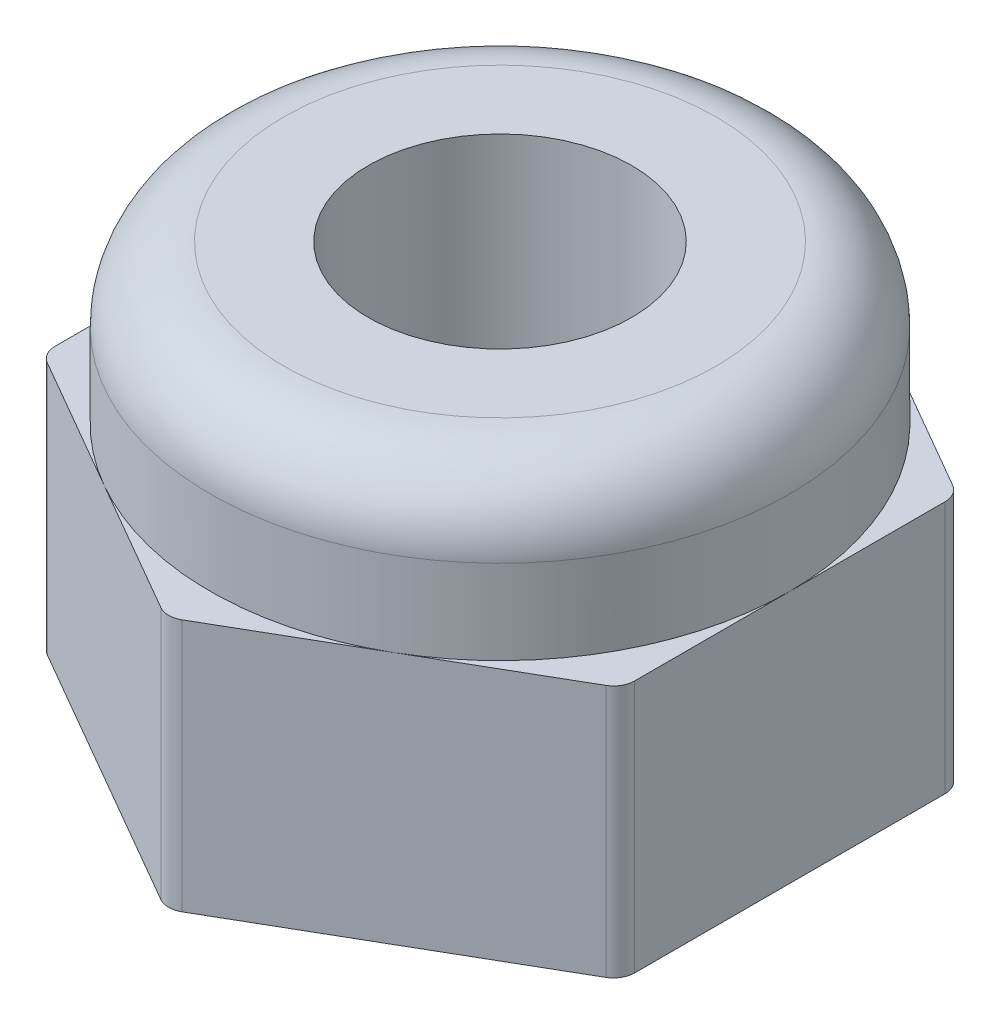
SolidWorks part; units mm, degrees
ref_plane "前视基准面" through (0, 0, 0) normal (0, 0, 1) x (1, 0, 0)
ref_plane "上视基准面" through (0, 0, 0) normal (0, 1, 0) x (1, 0, 0)
ref_plane "右视基准面" through (0, 0, 0) normal (1, 0, 0) x (0, 0, -1)
sketch "草图1" plane through (0, 0, 0) normal (0, 1, 0) x (1, 0, 0)
  line L1 (2.75, 1.5877) -> (0, 3.1754)
  line L2 (0, 3.1754) -> (-2.75, 1.5877)
  line L3 (-2.75, 1.5877) -> (-2.75, -1.5877)
  line L4 (-2.75, -1.5877) -> (0, -3.1754)
  line L5 (0, -3.1754) -> (2.75, -1.5877)
  line L6 (2.75, -1.5877) -> (2.75, 1.5877)
  circle A0 centre (0, 0) radius 2.75 construction
  dimension "D1" = 5.5
extrude "凸台-拉伸1" add sketch "草图1" along normal blind 2.4
sketch "草图2" plane through (0, 0, 0) normal (0, -1, 0) x (1, 0, 0)
  line L0 (2.75, 1.5877) -> (2.75, -1.5877) construction
  circle A0 centre (0, 0) radius 2.75
extrude "凸台-拉伸2" add sketch "草图2" against normal blind 3.9
fillet "圆角1" radius 0.7 1 edges at (0, 3.9, -2.75)
fillet "圆角2" radius 0.2 6 edges at (-2.75, 1.2, 1.5877) (-2.75, 1.2, -1.5877) (0, 1.2, -3.1754) (2.75, 1.2, -1.5877) (2.75, 1.2, 1.5877) (0, 1.2, 3.1754)
hole_wizard "M3 螺纹孔1" positions "草图3" profile "草图4" tap size "M3" standard "GB"
sketch "草图3" plane through (0, 0, 0) normal (0, -1, 0) x (-1, 0, 0)
  point P0 (0, 0)
cosmetic thread "孔螺蚊线1" parameters "D1"=6, "D2"=3
sketch "草图4" plane through (0, 0, 0) normal (1, 0, 0) x (0, 0, -1)
  line L0 (0, 0) -> (0, 8.2511)
  line L1 (0, 8.2511) -> (1.25, 7.5)
  line L2 (1.25, 7.5) -> (1.25, 0)
  line L5 (1.25, 0) -> (0, 0)
  line L10 (0, 8.2511) -> (-1.25, 7.5) construction
  line L11 (0, -6.35) -> (0, 107.95) construction
  dimension "螺纹孔钻头直径" = 2.5
  dimension "螺纹孔钻头深度" = 7.5
  dimension "导头角度" = 118
